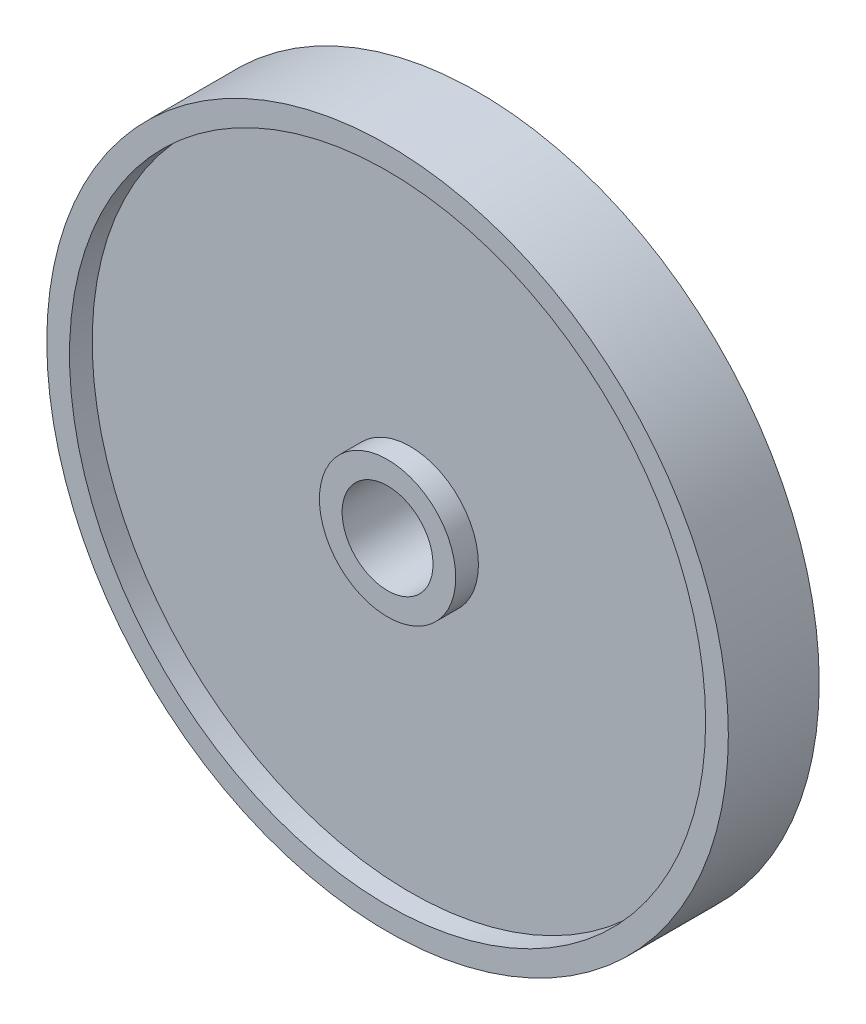
SolidWorks part; units mm, degrees
ref_plane "Front Plane" through (0, 0, 0) normal (0, 0, 1) x (1, 0, 0)
ref_plane "Top Plane" through (0, 0, 0) normal (0, 1, 0) x (1, 0, 0)
ref_plane "Right Plane" through (0, 0, 0) normal (1, 0, 0) x (0, 0, -1)
sketch "Sketch1" plane through (0, 0, 0) normal (0, 0, 1) x (1, 0, 0)
  line L0 (0, 18.2927) -> (0, -18.8538) construction
  line L1 (-27.3829, 0) -> (23.455, 0) construction
  circle A0 centre (0, 0) radius 5
  circle A1 centre (0, 0) radius 37.5
  dimension "D1" = 10
  dimension "D2" = 75
extrude "Boss-Extrude1" add sketch "Sketch1" along normal blind 10
sketch "Sketch2" plane through (0, 0, 10) normal (0, 0, 1) x (1, 0, 0)
  circle A0 centre (0, 0) radius 35
  circle A1 centre (0, 0) radius 7.5
  dimension "D1" = 70
  dimension "D2" = 15
extrude "Cut-Extrude1" cut sketch "Sketch2" against normal blind 2.5
sketch "Sketch3" plane through (0, 0, 0) normal (0, 0, -1) x (-1, 0, 0)
  circle A0 centre (0, 0) radius 7.5
  circle A1 centre (0, 0) radius 35
  dimension "D1" = 15
  dimension "D2" = 70
extrude "Cut-Extrude2" cut sketch "Sketch3" against normal blind 2.5
